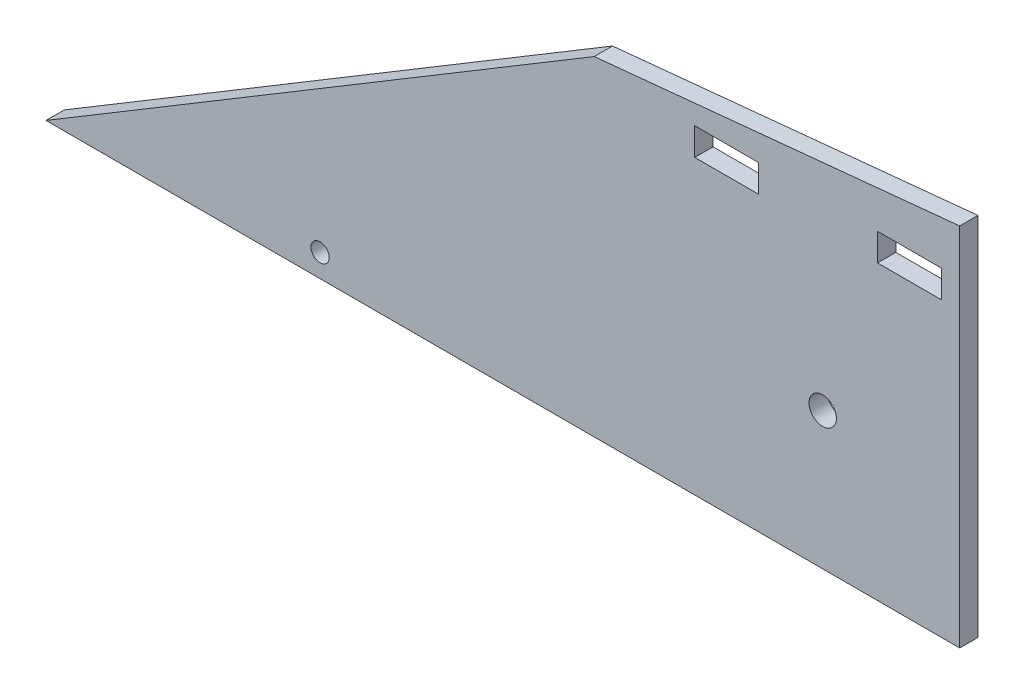
SolidWorks part; units mm, degrees
material "PBT 一般用途"
ref_plane "前视基准面" through (0, 0, 0) normal (0, 0, 1) x (1, 0, 0)
ref_plane "上视基准面" through (0, 0, 0) normal (0, 1, 0) x (1, 0, 0)
ref_plane "右视基准面" through (0, 0, 0) normal (1, 0, 0) x (0, 0, -1)
sketch "草图1" plane through (0, 0, 0) normal (0, 0, 1) x (1, 0, 0)
  line L0 (-938.6353, 0) -> (61.3647, 0)
  line L1 (61.3647, 0) -> (61.3647, 400)
  line L2 (61.3647, 400) -> (-338.6353, 360.5551)
  line L3 (-338.6353, 360.5551) -> (-938.6353, 0)
  dimension "D1" = 1000
  dimension "D2" = 400
  dimension "D3" = 400
  dimension "D4" = 700
extrude "凸台-拉伸1" add sketch "草图1" along normal blind 20
sketch "草图2" plane through (0, 0, 0) normal (0, 0, 1) x (1, 0, 0)
  line L1 (-158.6353, 320) -> (-228.6353, 320)
  line L2 (-158.6353, 320) -> (-158.6353, 350)
  line L3 (-158.6353, 350) -> (-228.6353, 350)
  line L4 (-228.6353, 320) -> (-228.6353, 350)
  line L5 (-158.6353, 320) -> (-228.6353, 350) construction
  line L6 (-158.6353, 350) -> (-228.6353, 320) construction
  line L7 (-938.6353, 0) -> (61.3647, 0) construction
  line L8 (61.3647, 0) -> (61.3647, 400) construction
  line L9 (-938.6353, 0) -> (61.3647, 0) construction
  line L10 (-28.6353, 320) -> (41.3647, 320)
  line L11 (-28.6353, 320) -> (-28.6353, 350)
  line L12 (-28.6353, 350) -> (41.3647, 350)
  line L13 (41.3647, 320) -> (41.3647, 350)
  line L14 (-28.6353, 320) -> (41.3647, 350) construction
  line L15 (-28.6353, 350) -> (41.3647, 320) construction
  circle A0 centre (-88.6353, 150) radius 15
  circle A1 centre (-638.6353, 25) radius 10
  point P2 (-193.6353, 335)
  point P15 (6.3647, 335)
  dimension "D1" = 30
  dimension "D2" = 20
  dimension "D3" = 150
  dimension "D4" = 150
  dimension "D5" = 25
  dimension "D6" = 700
  dimension "D7" = 70
  dimension "D8" = 30
  dimension "D9" = 290
  dimension "D10" = 320
  dimension "D11" = 70
  dimension "D12" = 30
  dimension "D13" = 90
extrude "切除-拉伸2" cut sketch "草图2" along normal up to surface (20 mm away) up to face at (-288.6353, 190.1388, 20)
